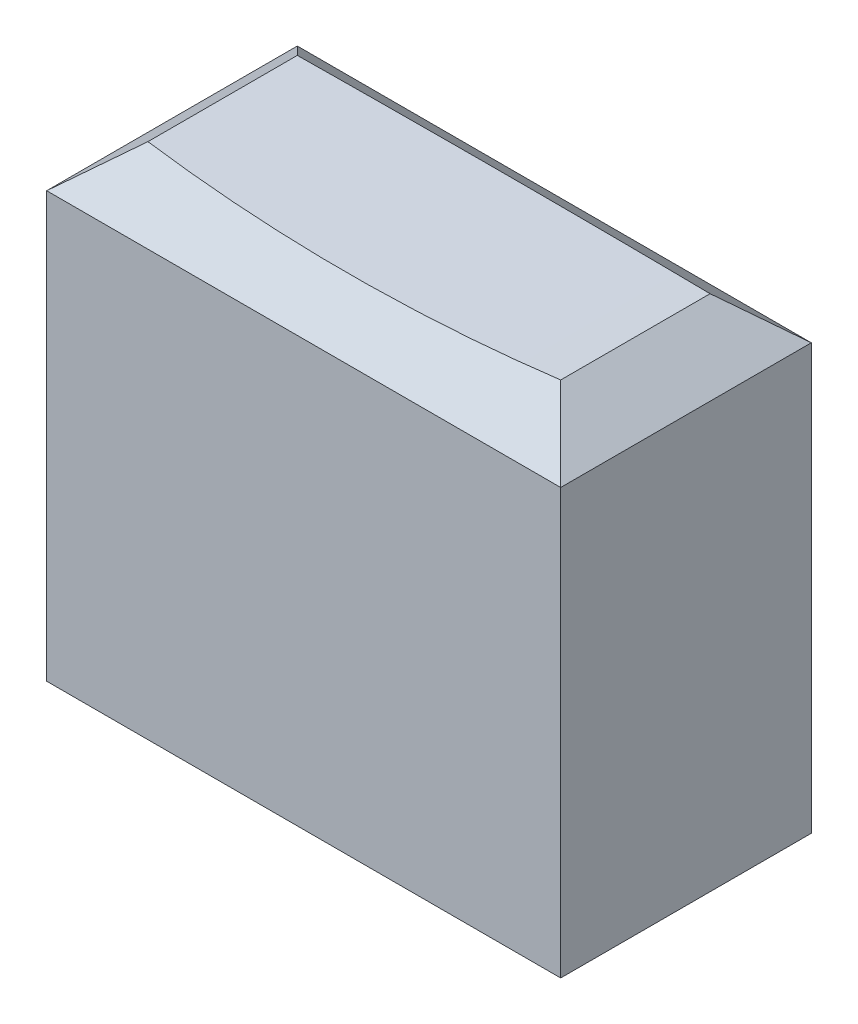
SolidWorks part; units mm, degrees
ref_plane "Front Plane" through (0, 0, 0) normal (0, 0, 1) x (1, 0, 0)
ref_plane "Top Plane" through (0, 0, 0) normal (0, 1, 0) x (1, 0, 0)
ref_plane "Right Plane" through (0, 0, 0) normal (1, 0, 0) x (0, 0, -1)
sketch "Sketch1" plane through (0, 0, 0) normal (0, 1, 0) x (1, 0, 0)
  line L1 (-6.05, 2.95) -> (6.05, 2.95)
  line L2 (-6.05, 2.95) -> (-6.05, -2.95)
  line L3 (-6.05, -2.95) -> (6.05, -2.95)
  line L4 (6.05, 2.95) -> (6.05, -2.95)
  point P4 (6.05, 0)
  point P6 (0, 2.95)
  dimension "D1" = 12.1
  dimension "D2" = 5.9
extrude "Boss-Extrude1" add sketch "Sketch1" along normal blind 11
chamfer "Chamfer1" distance 1 angle 50 4 edges at (0, 11, -2.95) (6.05, 11, 0) (0, 11, 2.95) (-6.05, 11, 0)
sketch "Sketch6" plane through (0, 0, 2.95) normal (0, 0, 1) x (1, 0, 0)
  line L0 (-4.8582, 11) -> (4.8582, 11) construction
  line L1 (-4.8582, 11) -> (4.8582, 11)
  line L2 (-4.8582, 10.85) -> (4.8582, 10.85) construction
  arc A0 (-4.8582, 11) -> (4.8582, 11) centre (0, 89.6002) ccw
  point P6 (0, 0)
  dimension "D1" = 0.3
extrude "Cut-Extrude3" cut sketch "Sketch6" against normal through all
sketch "Sketch7" plane through (0, 0, 0) normal (0, -1, 0) x (1, 0, 0)
  line L0 (-2.05, -1) -> (-2.05, -2.45)
  line L1 (-5.55, 2.45) -> (-2.05, 2.45)
  line L2 (-5.55, 2.45) -> (-5.55, -2.45)
  line L3 (-5.55, -2.45) -> (-2.05, -2.45)
  line L4 (-2.05, 2.45) -> (-2.05, 1)
  line L5 (2.05, 2.45) -> (5.55, 2.45)
  line L6 (2.05, 2.45) -> (2.05, 1)
  line L7 (2.05, -2.45) -> (5.55, -2.45)
  line L8 (5.55, 2.45) -> (5.55, -2.45)
  line L9 (-1.65, 1.65) -> (1.65, 1.65)
  line L10 (-1.65, 1.65) -> (-1.65, 1)
  line L11 (-1.65, -1.65) -> (1.65, -1.65)
  line L12 (1.65, 1.65) -> (1.65, 1)
  line L13 (-2.05, 1) -> (-1.65, 1)
  line L15 (-2.05, -1) -> (-1.65, -1)
  line L17 (-1.65, -1) -> (-1.65, -1.65)
  line L18 (1.65, -1) -> (1.65, -1.65)
  line L19 (2.05, -1) -> (2.05, -2.45)
  line L20 (1.65, 1) -> (2.05, 1)
  line L21 (1.65, -1) -> (2.05, -1)
  line L22 (-6.05, 2.95) -> (6.05, 2.95) construction
  line L23 (6.05, -2.95) -> (-6.05, -2.95) construction
  line L24 (-6.05, -2.95) -> (-6.05, 2.95) construction
  line L25 (6.05, 2.95) -> (6.05, -2.95) construction
  dimension "D1" = 0.5
  dimension "D2" = 0.5
  dimension "D3" = 0.5
  dimension "D4" = 0.5
  dimension "D5" = 3.3
  dimension "D6" = 0.4
  dimension "D7" = 3.3
  dimension "D8" = 2
extrude "Cut-Extrude4" cut sketch "Sketch7" against normal blind 9
